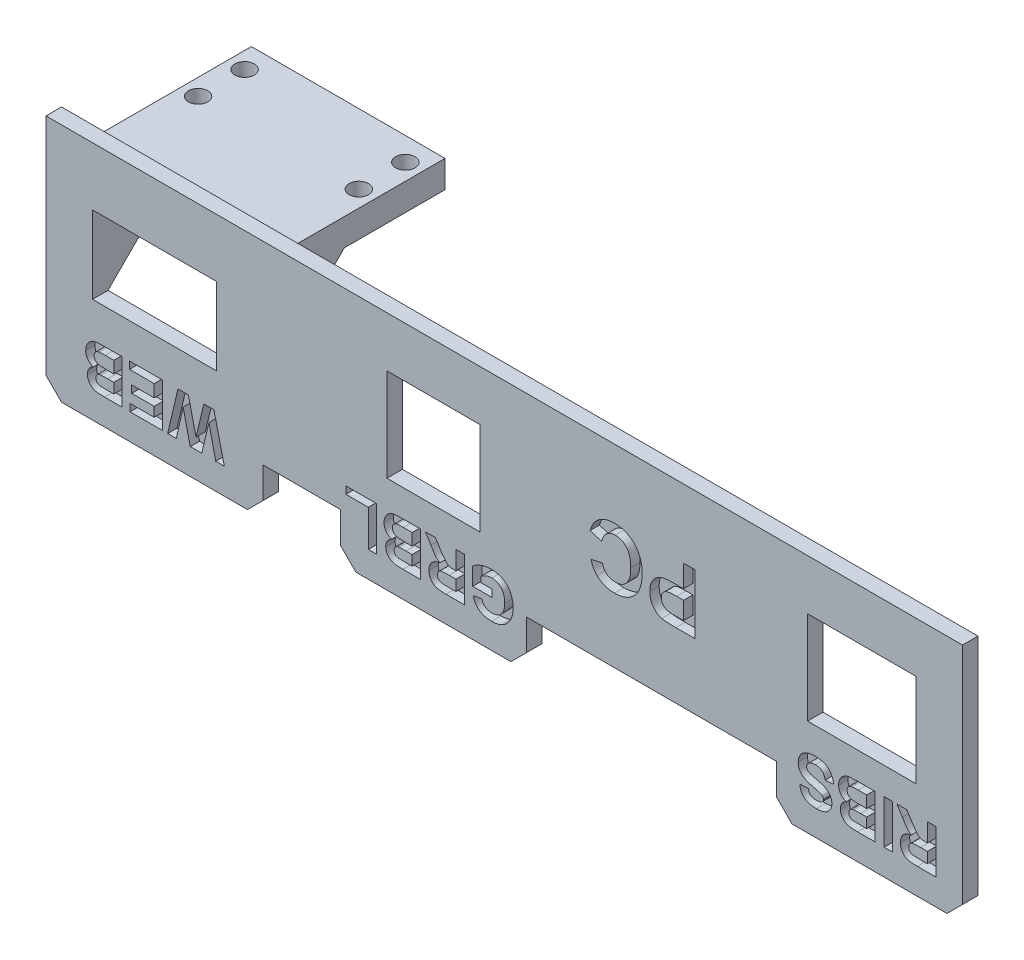
SolidWorks part; units mm, degrees
ref_plane "Спереди" through (0, 0, 0) normal (0, 0, 1) x (1, 0, 0)
ref_plane "Сверху" through (0, 0, 0) normal (0, 1, 0) x (1, 0, 0)
ref_plane "Справа" through (0, 0, 0) normal (1, 0, 0) x (0, 0, -1)
sketch "Эскиз1" plane through (0, 0, 0) normal (0, 0, 1) x (1, 0, 0)
  line L1 (-40, 12.5) -> (40, 12.5)
  line L2 (-40, 12.5) -> (-40, -12.5)
  line L3 (-40, -12.5) -> (40, -12.5)
  line L4 (40, 12.5) -> (40, -12.5)
  line L5 (-40, 12.5) -> (40, -12.5) construction
  line L6 (-40, -12.5) -> (40, 12.5) construction
  point P0 (0, 0)
  dimension "D1" = 80
  dimension "D2" = 25
extrude "Бобышка-Вытянуть1" add sketch "Эскиз1" along normal blind 2
sketch "Эскиз2" plane through (0, 0, 2) normal (0, 0, 1) x (1, 0, 0)
  line L0 (-40, 12.5) -> (27, 12.5)
  line L1 (40, 12.5) -> (-40, 12.5) construction
  line L2 (27, 12.5) -> (27, 0)
  line L3 (27, 12.5) -> (40, 12.5)
  line L4 (20, 6) -> (34, 6)
  line L5 (20, 6) -> (20, -6)
  line L6 (20, -6) -> (34, -6)
  line L7 (34, 6) -> (34, -6)
  line L8 (20, 6) -> (34, -6) construction
  line L9 (20, -6) -> (34, 6) construction
  dimension "D1" = 13
  dimension "D2" = 14
  dimension "D3" = 12
extrude "Вырез-Вытянуть2" cut sketch "Эскиз2" against normal through all
sketch "Эскиз3" plane through (0, 0, 0) normal (0, 0, -1) x (-1, 0, 0)
  line L0 (-20, -6) -> (-34, 6)
  line L1 (-27, 0) -> (28.28, 0)
  line L3 (22.28, 6) -> (34.28, 6)
  line L4 (22.28, 6) -> (22.28, -6)
  line L5 (22.28, -6) -> (34.28, -6)
  line L6 (34.28, 6) -> (34.28, -6)
  line L7 (22.28, 6) -> (34.28, -6) construction
  line L8 (22.28, -6) -> (34.28, 6) construction
  dimension "D1" = 55.28
  dimension "D2" = 12
  dimension "D3" = 12
extrude "Вырез-Вытянуть3" cut sketch "Эскиз3" against normal through all
sketch "Эскиз4" plane through (0, 0, 0) normal (0, 0, -1) x (-1, 0, 0)
  line L1 (40, 12.5) -> (80, 12.5)
  line L2 (40, 12.5) -> (40, -12.5)
  line L3 (40, -12.5) -> (80, -12.5)
  line L4 (80, 12.5) -> (80, -12.5)
  dimension "D1" = 40
extrude "Бобышка-Вытянуть2" add sketch "Эскиз4" against normal blind 2
sketch "Эскиз5" plane through (0, 0, 0) normal (0, 0, -1) x (-1, 0, 0)
  line L0 (34.28, 0) -> (64.28, 0)
  line L1 (34.28, 6) -> (34.28, -6) construction
  line L3 (56.28, 5) -> (72.28, 5)
  line L4 (56.28, 5) -> (56.28, -5)
  line L5 (56.28, -5) -> (72.28, -5)
  line L6 (72.28, 5) -> (72.28, -5)
  line L7 (56.28, 5) -> (72.28, -5) construction
  line L8 (56.28, -5) -> (72.28, 5) construction
  dimension "D1" = 30
  dimension "D2" = 10
  dimension "D3" = 16
extrude "Вырез-Вытянуть4" cut sketch "Эскиз5" against normal through all
sketch "Эскиз6" plane through (0, 0, 2) normal (0, 0, 1) x (1, 0, 0)
  line L0 (-56.28, -5) -> (-72.28, -5) construction
  line L1 (-51.78, 5) -> (-76.78, 5)
  line L2 (-51.78, 5) -> (-51.78, 8.5)
  line L3 (-51.78, 8.5) -> (-76.78, 8.5)
  line L4 (-76.78, 5) -> (-76.78, 8.5)
  line L5 (-56.28, 5) -> (-72.28, 5) construction
  point P4 (-64.28, 5)
  point P5 (-64.28, -5)
  dimension "D1" = 25
  dimension "D2" = 3.5
extrude "Бобышка-Вытянуть3" add sketch "Эскиз6" against normal blind 25
chamfer "Фаска1" distance 10 angle 45 2 edges at (-74.53, 5, 0) (-54.03, 5, 0)
sketch "Эскиз7" plane through (0, 5, 0) normal (0, -1, 0) x (1, 0, 0)
  line L0 (-51.78, -23) -> (-53.9088, -23)
  line L1 (-76.78, -23) -> (-51.78, -23) construction
  line L2 (-53.9088, -23) -> (-53.9088, -20)
  line L3 (-53.9088, -20) -> (-53.9088, -14)
  line L4 (-64.28, -23) -> (-64.28, -18.1669)
  circle A0 centre (-53.9088, -20) radius 1.25
  circle A1 centre (-53.9088, -14) radius 1.25
  circle A2 centre (-74.6512, -20) radius 1.25
  circle A3 centre (-74.6512, -14) radius 1.25
  dimension "D1" = 2.5
  dimension "D2" = 3
  dimension "D3" = 6
extrude "Вырез-Вытянуть5" cut sketch "Эскиз7" against normal through all
sketch "Эскиз8" plane through (0, 5, 0) normal (0, -1, 0) x (1, 0, 0)
  line L0 (-76.78, -23) -> (-51.78, -23) construction
  line L1 (-59.28, -23) -> (-69.28, -23)
  line L2 (-59.28, -23) -> (-59.28, -11)
  line L3 (-59.28, -11) -> (-69.28, -11)
  line L4 (-69.28, -23) -> (-69.28, -11)
  line L5 (-59.28, -23) -> (-51.78, -23)
  line M11 (-76.78, -23) -> (-51.78, -23)
  dimension "D1" = 10
  dimension "D2" = 7.5
  dimension "D3" = 12
extrude "Бобышка-Вытянуть4" add sketch "Эскиз8" along normal blind 1.5 contours L4 L2 L3 M11
sketch "Эскиз9" plane through (0, 0, 0) normal (0, 0, -1) x (-1, 0, 0)
  line L1 (76.78, 8.5) -> (80, 8.5)
  line L2 (80, -12.5) -> (80, 12.5) construction
  line L3 (80, 12.5) -> (82.78, 12.5)
  line L4 (82.78, 12.5) -> (82.78, -12.5)
  line L5 (82.78, -12.5) -> (80, -12.5)
  line L6 (80, 12.5) -> (80, -12.5)
  line M16 (80, -12.5) -> (80, 12.5)
  dimension "D1" = 2.78
extrude "Бобышка-Вытянуть5" add sketch "Эскиз9" against normal blind 2 contours L5 L4 L3 M16
sketch "Эскиз11" plane through (0, 0, 2) normal (0, 0, 1) x (1, 0, 0)
  line L0 (20, 6) -> (20, 3.6517)
  line L1 (20, 6) -> (20, -6) construction
  line L2 (20, 3.6517) -> (-22.28, 3.6517)
  line L3 (-22.28, 6) -> (-22.28, -6) construction
  line L4 (5.4784, 3.6517) -> (5.4784, -4.0532)
  line L5 (5.4784, -4.0532) -> (3.0135, -4.0532)
  line L6 (2.9826, 0.7871) -> (3.9966, 0.7871)
  line L7 (3.9966, 0.7871) -> (3.9966, 3.6517)
  line L8 (3.9966, 3.6517) -> (5.4784, 3.6517)
  line L9 (3.9966, -2.769) -> (3.9966, -0.4971)
  line L10 (3.9966, -0.4971) -> (3.1076, -0.4971)
  line L11 (3.2126, -2.769) -> (3.9966, -2.769)
  line L12 (-6.573, 0.7871) -> (-8.0547, 1.281)
  line L13 (-7.9559, -1.88) -> (-6.4742, -1.5837)
  spline S0 degree 3 poles (3.0135, -4.0532) (2.8004, -4.0541) (2.4958, -4.0501) (2.1099, -4.0372) (1.8659, -4.0258) (1.6529, -4.0088) (1.4287, -3.9845) (1.276, -3.9608) (1.186, -3.9359) knots 0 0 0 0 0.34833 0.498164 0.631258 0.747724 0.847597 1 1 1 1
  spline S1 degree 3 poles (1.186, -3.9359) (1.078, -3.9088) (0.9218, -3.8507) (0.7242, -3.7497) (0.5845, -3.6597) (0.4501, -3.559) (0.3239, -3.444) (0.2027, -3.3169) (0.0894, -3.1774) (-0.0152, -3.0261) (-0.1039, -2.8621) (-0.1803, -2.6883) (-0.2413, -2.5035) (-0.2918, -2.3089) (-0.336, -2.0278) (-0.352, -1.8106) (-0.3497, -1.6624) knots 0 0 0 0 0.112518 0.168209 0.224432 0.280596 0.338142 0.397105 0.458213 0.520063 0.583016 0.646708 0.712116 0.779846 0.850081 1 1 1 1
  spline S2 degree 3 poles (-0.3497, -1.6624) (-0.3521, -1.4412) (-0.322, -1.1202) (-0.2135, -0.719) (-0.0986, -0.4596) (0.0385, -0.2274) (0.1962, -0.0228) (0.3671, 0.1592) (0.5583, 0.3092) (0.7574, 0.4344) (1.0201, 0.5743) (1.2286, 0.6444) (1.3681, 0.676) knots 0 0 0 0 0.210528 0.305147 0.394439 0.479889 0.561317 0.639975 0.717023 0.791911 0.863787 1 1 1 1
  spline S3 degree 3 poles (1.3681, 0.676) (1.4709, 0.6962) (1.6332, 0.722) (1.8613, 0.745) (2.0553, 0.7604) (2.2653, 0.7724) (2.576, 0.7857) (2.8169, 0.7864) (2.9826, 0.7871) knots 0 0 0 0 0.193876 0.303997 0.424377 0.554128 0.693296 1 1 1 1
  spline S4 degree 3 poles (3.1076, -0.4971) (2.961, -0.4972) (2.7503, -0.4986) (2.4835, -0.5152) (2.3123, -0.5256) (2.1621, -0.5448) (2.031, -0.5655) (1.9201, -0.5913) (1.7998, -0.6296) (1.6704, -0.6903) (1.5328, -0.7803) (1.4129, -0.8892) (1.3124, -1.015) (1.2314, -1.1542) (1.1537, -1.3603) (1.1301, -1.5265) (1.132, -1.6392) knots 0 0 0 0 0.168841 0.242402 0.307726 0.366205 0.416644 0.460461 0.497174 0.561832 0.624256 0.685892 0.747405 0.808969 0.870459 1 1 1 1
  spline S5 degree 3 poles (1.132, -1.6392) (1.1295, -1.7745) (1.1613, -1.9734) (1.2711, -2.2121) (1.3855, -2.3636) (1.5232, -2.4915) (1.7343, -2.6315) (1.9172, -2.6915) (2.0426, -2.715) knots 0 0 0 0 0.263219 0.386149 0.508701 0.630747 0.750909 1 1 1 1
  spline S6 degree 3 poles (2.0426, -2.715) (2.1029, -2.7257) (2.2033, -2.7371) (2.3497, -2.7483) (2.4871, -2.7559) (2.6425, -2.7618) (2.8863, -2.7689) (3.0783, -2.7668) (3.2126, -2.769) knots 0 0 0 0 0.156655 0.258348 0.375719 0.50881 0.656332 1 1 1 1
  spline S7 degree 3 poles (-8.0547, 1.281) (-7.9986, 1.4719) (-7.9019, 1.7495) (-7.7339, 2.0943) (-7.5966, 2.3285) (-7.4444, 2.5425) (-7.2794, 2.7385) (-7.0976, 2.9133) (-6.9024, 3.07) (-6.6931, 3.2079) (-6.4698, 3.3271) (-6.2331, 3.4274) (-5.9826, 3.5092) (-5.7191, 3.5744) (-5.3414, 3.6336) (-5.0502, 3.6526) (-4.852, 3.6517) knots 0 0 0 0 0.13791 0.202925 0.265376 0.325683 0.384581 0.442536 0.500073 0.557687 0.615869 0.675098 0.735491 0.79823 0.86284 1 1 1 1
  spline S8 degree 3 poles (-4.852, 3.6517) (-4.6058, 3.6534) (-4.2424, 3.6218) (-3.7772, 3.5128) (-3.4505, 3.402) (-3.142, 3.2556) (-2.8507, 3.0776) (-2.5771, 2.8669) (-2.3218, 2.6274) (-2.0903, 2.3594) (-1.8884, 2.0651) (-1.7167, 1.7482) (-1.5772, 1.4071) (-1.4693, 1.0424) (-1.365, 0.5122) (-1.3374, 0.0981) (-1.3376, -0.1838) knots 0 0 0 0 0.126041 0.185858 0.244347 0.302332 0.360396 0.418837 0.478855 0.539381 0.599819 0.661239 0.723621 0.788224 0.855654 1 1 1 1
  spline S9 degree 3 poles (-1.3376, -0.1838) (-1.3381, -0.4808) (-1.3636, -0.9163) (-1.47, -1.4727) (-1.5744, -1.8541) (-1.7154, -2.2079) (-1.8822, -2.5377) (-2.0856, -2.8385) (-2.3145, -3.1134) (-2.5699, -3.3574) (-2.846, -3.5705) (-3.142, -3.7497) (-3.4567, -3.8983) (-3.7914, -4.0118) (-4.2725, -4.124) (-4.6495, -4.1498) (-4.9045, -4.152) knots 0 0 0 0 0.147861 0.216121 0.281505 0.344236 0.405241 0.465004 0.524411 0.582874 0.640357 0.697546 0.754672 0.813104 0.873008 1 1 1 1
  spline S10 degree 3 poles (-4.9045, -4.152) (-5.1274, -4.1499) (-5.4566, -4.1292) (-5.8782, -4.0388) (-6.1714, -3.9454) (-6.4496, -3.8288) (-6.7976, -3.6334) (-7.0329, -3.4474) (-7.1765, -3.3093) knots 0 0 0 0 0.269237 0.396245 0.519357 0.640091 0.759611 1 1 1 1
  spline S11 degree 3 poles (-7.1765, -3.3093) (-7.2664, -3.2251) (-7.3882, -3.0827) (-7.5337, -2.8745) (-7.6349, -2.7019) (-7.7277, -2.5155) (-7.843, -2.2435) (-7.9148, -2.0286) (-7.9559, -1.88) knots 0 0 0 0 0.22393 0.340378 0.462188 0.5879 0.719301 1 1 1 1
  spline S12 degree 3 poles (-6.4742, -1.5837) (-6.4516, -1.68) (-6.4071, -1.8196) (-6.329, -1.9961) (-6.2577, -2.1164) (-6.1819, -2.2319) (-6.0921, -2.3367) (-5.9957, -2.436) (-5.8887, -2.5253) (-5.7741, -2.6058) (-5.6531, -2.6766) (-5.5253, -2.7358) (-5.3917, -2.7831) (-5.2528, -2.8228) (-5.0555, -2.8565) (-4.904, -2.8703) (-4.8011, -2.8678) knots 0 0 0 0 0.129401 0.191503 0.25216 0.312317 0.372084 0.432576 0.493292 0.554214 0.615791 0.676668 0.738245 0.801163 0.865508 1 1 1 1
  spline S13 degree 3 poles (-4.8011, -2.8678) (-4.6597, -2.8695) (-4.452, -2.8488) (-4.1856, -2.7872) (-4.0002, -2.7201) (-3.826, -2.633) (-3.6604, -2.5295) (-3.5076, -2.4046) (-3.3639, -2.2624) (-3.2352, -2.0972) (-3.1219, -1.9095) (-3.028, -1.6971) (-2.9517, -1.4621) (-2.8917, -1.2039) (-2.8322, -0.8142) (-2.8216, -0.5075) (-2.8193, -0.2964) knots 0 0 0 0 0.114852 0.169049 0.221995 0.274766 0.327238 0.380498 0.43494 0.491274 0.550406 0.612776 0.679731 0.751083 0.828135 1 1 1 1
  spline S14 degree 3 poles (-2.8193, -0.2964) (-2.8217, -0.0735) (-2.8318, 0.2496) (-2.8919, 0.6603) (-2.9508, 0.9306) (-3.028, 1.1752) (-3.1221, 1.3942) (-3.2321, 1.5889) (-3.3626, 1.7558) (-3.5059, 1.8998) (-3.6586, 2.0256) (-3.8224, 2.1314) (-3.996, 2.2187) (-4.1808, 2.2846) (-4.4448, 2.35) (-4.6516, 2.3685) (-4.7918, 2.3676) knots 0 0 0 0 0.177674 0.256759 0.330211 0.397713 0.460651 0.519748 0.575226 0.628818 0.681222 0.73247 0.78377 0.835607 0.888367 1 1 1 1
  spline S15 degree 3 poles (-4.7918, 2.3676) (-4.8959, 2.3661) (-5.0513, 2.3583) (-5.2512, 2.3156) (-5.3936, 2.274) (-5.5311, 2.2217) (-5.6617, 2.1546) (-5.7877, 2.0776) (-5.9067, 1.9872) (-6.0203, 1.8858) (-6.1238, 1.7686) (-6.2199, 1.6385) (-6.3072, 1.4944) (-6.3887, 1.3378) (-6.4839, 1.1028) (-6.5426, 0.9167) (-6.573, 0.7871) knots 0 0 0 0 0.120461 0.178741 0.235724 0.291792 0.348406 0.404979 0.462271 0.52076 0.580529 0.642578 0.707405 0.77492 0.84633 1 1 1 1
extrude "Вырез-Вытянуть6" cut sketch "Эскиз11" against normal blind 1.2 contours S3 S2 S1 S0 L5 L4 L2 L7 L6 S6 S5 S4 L10 L9 L11 | S15 S14 S13 S12 L13 S11 S10 S9 S8 L2 S7 L12
sketch "Эскиз12" plane through (0, 0, 2) normal (0, 0, 1) x (1, 0, 0)
  line L0 (40, -12.5) -> (40, -18.5)
  line L1 (40, -18.5) -> (16, -18.5)
  line L2 (16, -18.5) -> (16, -12.5)
  line L3 (-82.78, -12.5) -> (40, -12.5) construction
  line L4 (16, -12.5) -> (-16.28, -12.5)
  line L5 (-16.28, -12.5) -> (-16.28, -18.5)
  line L6 (-16.28, -18.5) -> (-40.28, -18.5)
  line L7 (-40.28, -18.5) -> (-40.28, -12.5)
  line L8 (-40.28, -12.5) -> (-50.28, -12.5)
  line L9 (-50.28, -12.5) -> (-50.28, -18.5)
  line L10 (-50.28, -18.5) -> (-82.78, -18.5)
  line L11 (-82.78, -18.5) -> (-82.78, -12.5)
  line L13 (-22.28, 6) -> (-22.28, -6) construction
  line L14 (-34.28, 6) -> (-34.28, -6) construction
  line L15 (-56.28, 5) -> (-56.28, -5) construction
  line L16 (40, -12.5) -> (-82.78, -12.5)
  line M13 (-82.78, -12.5) -> (40, -12.5)
  dimension "D1" = 24
  dimension "D2" = 6
  dimension "D3" = 6
  dimension "D4" = 6
  dimension "D5" = 6
  dimension "D6" = 6
  dimension "D7" = 6
extrude "Бобышка-Вытянуть6" add sketch "Эскиз12" against normal blind 2 contours L2 L1 L0 M13 | L7 L6 L5 M13 | L11 L10 L9 M13
sketch "Эскиз13" plane through (0, 0, 2) normal (0, 0, 1) x (1, 0, 0)
  line L0 (-78.28, 12.5) -> (-78.28, -18.5)
  line L1 (40, 12.5) -> (-82.78, 12.5) construction
  line L2 (-50.28, -18.5) -> (-82.78, -18.5) construction
  line L3 (-72.28, 5) -> (-72.28, -5) construction
  line L5 (-78.28, -18.5) -> (-82.78, -18.5)
  line L6 (-78.28, -18.5) -> (-78.28, 12.5)
  line L7 (-78.28, 12.5) -> (-82.78, 12.5)
  line L8 (-82.78, -18.5) -> (-82.78, 12.5)
  line M7 (40, 12.5) -> (-82.78, 12.5)
  line M8 (-82.78, 12.5) -> (-82.78, -18.5)
  line M9 (-82.78, -18.5) -> (-50.28, -18.5)
  dimension "D1" = 6
extrude "Вырез-Вытянуть7" cut sketch "Эскиз13" against normal through all contours L0 M7 M8 M9
chamfer "Фаска2" distance 2 angle 45 6 edges at (40, -18.5, 1) (16, -18.5, 1) (-16.28, -18.5, 1) (-40.28, -18.5, 1) (-50.28, -18.5, 1) (-78.28, -18.5, 1)
sketch "Эскиз14" plane through (0, 0, 2) normal (0, 0, 1) x (1, 0, 0)
  line L5 (-16.28, -12.5) -> (-16.28, -9.5)
  line L10 (36.5479, -9.5) -> (36.5479, -15.1503)
  line L11 (36.5479, -15.1503) -> (34.1766, -15.1503)
  line L12 (32.2343, -10.6183) -> (31.5495, -9.5)
  line L13 (31.5495, -9.5) -> (32.8195, -9.5)
  line L14 (32.8195, -9.5) -> (33.6231, -10.7824)
  line L15 (35.2179, -11.8905) -> (35.4613, -11.8905)
  line L16 (35.4613, -11.8905) -> (35.4613, -9.5)
  line L17 (35.4613, -9.5) -> (36.5479, -9.5)
  line L18 (35.4613, -12.8322) -> (34.5864, -12.8322)
  line L19 (34.5377, -14.2086) -> (35.4613, -14.2086)
  line L20 (35.4613, -14.2086) -> (35.4613, -12.8322)
  line L21 (30.97, -9.5) -> (30.97, -15.1503)
  line L22 (30.97, -15.1503) -> (29.8834, -15.1503)
  line L23 (29.8834, -15.1503) -> (29.8834, -9.5)
  line L24 (29.8834, -9.5) -> (30.97, -9.5)
  line L25 (28.7244, -15.1503) -> (26.4482, -15.1503)
  line L26 (26.8115, -9.5) -> (28.7244, -9.5)
  line L27 (28.7244, -9.5) -> (28.7244, -15.1503)
  line L28 (27.6378, -14.2086) -> (27.6378, -12.9047)
  line L29 (27.6378, -12.9047) -> (26.8512, -12.9047)
  line L30 (26.9485, -14.2086) -> (27.6378, -14.2086)
  line L31 (27.6378, -11.963) -> (27.6378, -10.4417)
  line L32 (27.6378, -10.4417) -> (26.5286, -10.4417)
  line L33 (26.6701, -11.963) -> (27.6378, -11.963)
  line L34 (23.3639, -11.3834) -> (22.2773, -11.4559)
  line L35 (19.0175, -13.5566) -> (20.1041, -13.4842)
  line L36 (-20.7463, -11.6008) -> (-20.7463, -12.5425)
  line L37 (-20.7463, -12.5425) -> (-23.2092, -12.5425)
  line L38 (-23.2092, -12.5425) -> (-23.2092, -10.2731)
  line L39 (-23.1368, -13.5566) -> (-22.0502, -13.3393)
  line L40 (-22.1226, -10.8639) -> (-22.1226, -11.6008)
  line L41 (-22.1226, -11.6008) -> (-20.7463, -11.6008)
  line L42 (-24.2958, -9.5) -> (-24.2958, -15.1503)
  line L43 (-24.2958, -15.1503) -> (-26.6671, -15.1503)
  line L44 (-28.6094, -10.6183) -> (-29.2942, -9.5)
  line L45 (-29.2942, -9.5) -> (-28.0242, -9.5)
  line L46 (-28.0242, -9.5) -> (-27.2206, -10.7824)
  line L47 (-25.6258, -11.8905) -> (-25.3824, -11.8905)
  line L48 (-25.3824, -11.8905) -> (-25.3824, -9.5)
  line L49 (-25.3824, -9.5) -> (-24.2958, -9.5)
  line L50 (-25.3824, -12.8322) -> (-26.2573, -12.8322)
  line L51 (-26.306, -14.2086) -> (-25.3824, -14.2086)
  line L52 (-25.3824, -14.2086) -> (-25.3824, -12.8322)
  line L53 (-29.9461, -15.1503) -> (-32.2223, -15.1503)
  line L54 (-31.859, -9.5) -> (-29.9461, -9.5)
  line L55 (-29.9461, -9.5) -> (-29.9461, -15.1503)
  line L56 (-31.0327, -14.2086) -> (-31.0327, -12.9047)
  line L57 (-31.0327, -12.9047) -> (-31.8194, -12.9047)
  line L58 (-31.722, -14.2086) -> (-31.0327, -14.2086)
  line L59 (-31.0327, -11.963) -> (-31.0327, -10.4417)
  line L60 (-31.0327, -10.4417) -> (-32.1419, -10.4417)
  line L61 (-32.0005, -11.963) -> (-31.0327, -11.963)
  line L62 (-35.5964, -9.5) -> (-35.5964, -15.1503)
  line L63 (-35.5964, -15.1503) -> (-36.683, -15.1503)
  line L64 (-36.683, -15.1503) -> (-36.683, -10.4417)
  line L65 (-36.683, -10.4417) -> (-39.5806, -10.4417)
  line L66 (-39.5806, -10.4417) -> (-39.5806, -9.5)
  line L67 (-39.5806, -9.5) -> (-35.5964, -9.5)
  line L68 (-56.6138, -9.5) -> (-55.2613, -15.1503)
  line L69 (-55.2613, -15.1503) -> (-56.375, -15.1503)
  line L70 (-56.375, -15.1503) -> (-57.2533, -11.2691)
  line L71 (-57.2533, -11.2691) -> (-58.1826, -15.1503)
  line L72 (-58.1826, -15.1503) -> (-59.6654, -15.1503)
  line L73 (-59.6654, -15.1503) -> (-60.5856, -11.2035)
  line L74 (-60.5856, -11.2035) -> (-61.4616, -15.1503)
  line L75 (-61.4616, -15.1503) -> (-62.5777, -15.1503)
  line L76 (-62.5777, -15.1503) -> (-61.25, -9.5)
  line L77 (-61.25, -9.5) -> (-59.9042, -9.5)
  line L78 (-59.9042, -9.5) -> (-58.9195, -13.7241)
  line L79 (-58.9195, -13.7241) -> (-57.9087, -9.5)
  line L80 (-57.9087, -9.5) -> (-56.6138, -9.5)
  line L81 (-63.2296, -9.5) -> (-63.2296, -15.1503)
  line L82 (-63.2296, -15.1503) -> (-67.4311, -15.1503)
  line L83 (-67.4311, -15.1503) -> (-67.4311, -14.2086)
  line L84 (-67.4311, -14.2086) -> (-64.3162, -14.2086)
  line L85 (-64.3162, -14.2086) -> (-64.3162, -12.9771)
  line L86 (-64.3162, -12.9771) -> (-67.2138, -12.9771)
  line L87 (-67.2138, -12.9771) -> (-67.2138, -12.0354)
  line L88 (-67.2138, -12.0354) -> (-64.3162, -12.0354)
  line L89 (-64.3162, -12.0354) -> (-64.3162, -10.4417)
  line L90 (-64.3162, -10.4417) -> (-67.5036, -10.4417)
  line L91 (-67.5036, -10.4417) -> (-67.5036, -9.5)
  line L92 (-67.5036, -9.5) -> (-63.2296, -9.5)
  line L93 (-68.4453, -15.1503) -> (-70.7215, -15.1503)
  line L94 (-70.3581, -9.5) -> (-68.4453, -9.5)
  line L95 (-68.4453, -9.5) -> (-68.4453, -15.1503)
  line L96 (-69.5319, -14.2086) -> (-69.5319, -12.9047)
  line L97 (-69.5319, -12.9047) -> (-70.3185, -12.9047)
  line L98 (-70.2212, -14.2086) -> (-69.5319, -14.2086)
  line L99 (-69.5319, -11.963) -> (-69.5319, -10.4417)
  line L100 (-69.5319, -10.4417) -> (-70.6411, -10.4417)
  line L101 (-70.4996, -11.963) -> (-69.5319, -11.963)
  line L102 (-25.3824, -12.8322) -> (-25.3824, -14.2086)
  spline S0 degree 3 poles (34.1766, -15.1503) (34.0378, -15.1496) (33.8367, -15.1479) (33.5796, -15.1297) (33.4092, -15.1149) (33.254, -15.0932) (33.1138, -15.0677) (32.9889, -15.0375) (32.878, -15.002) (32.7772, -14.9605) (32.6831, -14.912) (32.5946, -14.8548) (32.5106, -14.7912) (32.4309, -14.7211) (32.3574, -14.6427) (32.2891, -14.557) (32.226, -14.4649) (32.1703, -14.3667) (32.1195, -14.2656) (32.0781, -14.1605) (32.0439, -14.0519) (32.0166, -13.9401) (31.9909, -13.7844) (31.9837, -13.6651) (31.9842, -13.5849) knots 0 0 0 0 0.134565 0.194651 0.249722 0.300282 0.346384 0.387789 0.424666 0.459085 0.493256 0.527124 0.561048 0.595231 0.629883 0.664994 0.701292 0.737973 0.774267 0.810855 0.847273 0.884511 0.922312 1 1 1 1
  spline S1 degree 3 poles (31.9842, -13.5849) (31.9835, -13.4845) (31.9956, -13.3366) (32.0312, -13.1452) (32.0714, -13.0117) (32.1214, -12.8847) (32.1824, -12.7649) (32.2545, -12.6514) (32.3379, -12.5456) (32.4324, -12.4474) (32.5384, -12.3589) (32.6553, -12.2791) (32.784, -12.2106) (32.9224, -12.1502) (33.1272, -12.0822) (33.2895, -12.0483) (33.4013, -12.0309) knots 0 0 0 0 0.129371 0.190807 0.250677 0.308758 0.366624 0.423704 0.481897 0.540034 0.599076 0.659654 0.722117 0.786819 0.85404 1 1 1 1
  spline S2 degree 3 poles (33.4013, -12.0309) (33.2918, -11.9619) (33.1381, -11.8489) (32.9546, -11.6812) (32.8514, -11.572) (32.775, -11.4742) (32.7109, -11.3905) (32.6432, -11.2928) (32.5716, -11.1818) (32.4927, -11.0596) (32.3788, -10.8709) (32.2926, -10.7221) (32.2343, -10.6183) knots 0 0 0 0 0.209166 0.307622 0.401733 0.451661 0.508279 0.572256 0.643667 0.721858 0.807553 1 1 1 1
  spline S3 degree 3 poles (33.6231, -10.7824) (33.6933, -10.8807) (33.7949, -11.0201) (33.9245, -11.1957) (34.0094, -11.304) (34.0817, -11.3999) (34.148, -11.4784) (34.2029, -11.5441) (34.2653, -11.609) (34.3373, -11.6763) (34.4281, -11.7389) (34.5184, -11.793) (34.6178, -11.8319) (34.7323, -11.8591) (34.9337, -11.8851) (35.0989, -11.8919) (35.2179, -11.8905) knots 0 0 0 0 0.174866 0.24983 0.316058 0.374091 0.423761 0.464831 0.498066 0.554153 0.607062 0.657484 0.706287 0.760884 0.827646 1 1 1 1
  spline S4 degree 3 poles (34.5864, -12.8322) (34.4577, -12.8315) (34.2747, -12.8352) (34.0441, -12.84) (33.9011, -12.8487) (33.778, -12.8569) (33.6749, -12.868) (33.5916, -12.8809) (33.5084, -12.9011) (33.4232, -12.9362) (33.3325, -12.9863) (33.2543, -13.0511) (33.1884, -13.1272) (33.1356, -13.2143) (33.0838, -13.3489) (33.0713, -13.4597) (33.0708, -13.5351) knots 0 0 0 0 0.202213 0.28763 0.362457 0.427262 0.481544 0.52541 0.559637 0.615792 0.669702 0.721935 0.77448 0.827155 0.881221 1 1 1 1
  spline S5 degree 3 poles (33.0708, -13.5351) (33.0711, -13.6189) (33.0878, -13.7423) (33.1552, -13.889) (33.2257, -13.9808) (33.3146, -14.0575) (33.4602, -14.1422) (33.5866, -14.1764) (33.6741, -14.1905) knots 0 0 0 0 0.256156 0.373043 0.488836 0.606317 0.729101 1 1 1 1
  spline S6 degree 3 poles (33.6741, -14.1905) (33.7098, -14.1952) (33.7729, -14.198) (33.8687, -14.2024) (33.968, -14.2041) (34.0849, -14.2068) (34.277, -14.2076) (34.4298, -14.2095) (34.5377, -14.2086) knots 0 0 0 0 0.124813 0.21921 0.333205 0.469464 0.625352 1 1 1 1
  spline S7 degree 3 poles (26.4482, -15.1503) (26.3426, -15.1494) (26.1893, -15.1494) (25.9924, -15.1426) (25.8607, -15.1374) (25.7399, -15.1297) (25.6298, -15.1193) (25.5305, -15.1081) (25.4131, -15.0924) (25.2776, -15.0615) (25.1238, -15.0108) (24.979, -14.9444) (24.8424, -14.8643) (24.7163, -14.7676) (24.6018, -14.6556) (24.4965, -14.5304) (24.4044, -14.391) (24.3276, -14.2393) (24.2547, -14.0198) (24.2329, -13.8458) (24.2331, -13.7287) knots 0 0 0 0 0.10585 0.153503 0.197393 0.237927 0.274751 0.30823 0.338007 0.393399 0.447191 0.499968 0.552674 0.605523 0.65872 0.712927 0.769123 0.825755 0.882774 1 1 1 1
  spline S8 degree 3 poles (24.2331, -13.7287) (24.2311, -13.5996) (24.2596, -13.4085) (24.3445, -13.1663) (24.4356, -12.9979) (24.5467, -12.8424) (24.7243, -12.6612) (24.8829, -12.555) (24.9983, -12.5029) knots 0 0 0 0 0.253072 0.37677 0.502927 0.628361 0.751685 1 1 1 1
  spline S9 degree 3 poles (24.9983, -12.5029) (24.9222, -12.4782) (24.8114, -12.436) (24.6743, -12.3617) (24.5796, -12.3009) (24.491, -12.2339) (24.4113, -12.1583) (24.3357, -12.0786) (24.2693, -11.9906) (24.2093, -11.8987) (24.1583, -11.8013) (24.1141, -11.7008) (24.0772, -11.5962) (24.0509, -11.4868) (24.0224, -11.3346) (24.0174, -11.2167) (24.0158, -11.1378) knots 0 0 0 0 0.132557 0.19578 0.258217 0.318868 0.379478 0.440087 0.500739 0.561785 0.621919 0.682673 0.743576 0.805446 0.868975 1 1 1 1
  spline S10 degree 3 poles (24.0158, -11.1378) (24.0165, -11.01) (24.0378, -10.8173) (24.1126, -10.5689) (24.1903, -10.3872) (24.2862, -10.2148) (24.4011, -10.0592) (24.5314, -9.9213) (24.6786, -9.8027) (24.8434, -9.7029) (25.0946, -9.5964) (25.3004, -9.5535) (25.442, -9.5385) knots 0 0 0 0 0.162582 0.244721 0.329221 0.413447 0.495126 0.574555 0.654073 0.734809 0.818867 1 1 1 1
  spline S11 degree 3 poles (25.442, -9.5385) (25.506, -9.5328) (25.6146, -9.525) (25.7762, -9.5189) (25.9347, -9.5129) (26.1184, -9.5086) (26.4135, -9.5043) (26.6474, -9.5005) (26.8115, -9.5) knots 0 0 0 0 0.140766 0.238316 0.354022 0.487867 0.640687 1 1 1 1
  spline S12 degree 3 poles (26.8512, -12.9047) (26.7455, -12.9038) (26.5953, -12.9055) (26.4059, -12.9066) (26.2886, -12.9087) (26.1879, -12.9123) (26.0871, -12.9164) (26.0198, -12.9194) (25.9807, -12.9239) knots 0 0 0 0 0.363929 0.517302 0.652498 0.76824 0.864499 1 1 1 1
  spline S13 degree 3 poles (25.9807, -12.9239) (25.8867, -12.9355) (25.7503, -12.9645) (25.5906, -13.0463) (25.4938, -13.1228) (25.4146, -13.2128) (25.3391, -13.3579) (25.3198, -13.4819) (25.3197, -13.5657) knots 0 0 0 0 0.279096 0.404007 0.523952 0.639469 0.753487 1 1 1 1
  spline S14 degree 3 poles (25.3197, -13.5657) (25.318, -13.6464) (25.3369, -13.7641) (25.4012, -13.9053) (25.469, -13.9948) (25.5567, -14.0688) (25.7039, -14.1512) (25.834, -14.1769) (25.923, -14.1893) knots 0 0 0 0 0.250494 0.364336 0.479021 0.596291 0.718617 1 1 1 1
  spline S15 degree 3 poles (25.923, -14.1893) (25.9667, -14.194) (26.0426, -14.1969) (26.1581, -14.201) (26.2758, -14.2045) (26.4146, -14.2067) (26.641, -14.2077) (26.8213, -14.2095) (26.9485, -14.2086) knots 0 0 0 0 0.12824 0.222081 0.337978 0.472602 0.628175 1 1 1 1
  spline S16 degree 3 poles (26.5286, -10.4417) (26.4304, -10.4399) (26.2905, -10.4437) (26.1139, -10.4453) (26.0034, -10.4507) (25.9079, -10.4547) (25.8098, -10.4608) (25.7444, -10.4704) (25.7057, -10.4768) knots 0 0 0 0 0.356994 0.509418 0.64271 0.759541 0.857263 1 1 1 1
  spline S17 degree 3 poles (25.7057, -10.4768) (25.6212, -10.4903) (25.5005, -10.5308) (25.3579, -10.6188) (25.2675, -10.7018) (25.1917, -10.7998) (25.12, -10.9601) (25.1013, -11.0945) (25.1024, -11.1865) knots 0 0 0 0 0.250355 0.369204 0.489075 0.608393 0.730225 1 1 1 1
  spline S18 degree 3 poles (25.1024, -11.1865) (25.1012, -11.2669) (25.1178, -11.3843) (25.1714, -11.5293) (25.2288, -11.6243) (25.3024, -11.7073) (25.3894, -11.7798) (25.4918, -11.8387) (25.5892, -11.8778) (25.6815, -11.9034) (25.7704, -11.9177) (25.8766, -11.9331) (26.001, -11.9433) (26.1429, -11.9529) (26.3678, -11.9593) (26.5455, -11.9644) (26.6701, -11.963) knots 0 0 0 0 0.120653 0.176517 0.231509 0.286607 0.342632 0.401132 0.463522 0.500008 0.544982 0.598838 0.661524 0.732611 0.812684 1 1 1 1
  spline S19 degree 3 poles (22.2773, -11.4559) (22.2628, -11.3671) (22.23, -11.2399) (22.1731, -11.079) (22.1245, -10.971) (22.0687, -10.8725) (22.0082, -10.7818) (21.9383, -10.7027) (21.863, -10.6317) (21.7813, -10.569) (21.6922, -10.5157) (21.5967, -10.4704) (21.4945, -10.4327) (21.3848, -10.4047) (21.2261, -10.3773) (21.1026, -10.3696) (21.0186, -10.3693) knots 0 0 0 0 0.146276 0.213514 0.277578 0.338921 0.39771 0.454752 0.510385 0.566047 0.621994 0.679152 0.738044 0.798989 0.863227 1 1 1 1
  spline S20 degree 3 poles (21.0186, -10.3693) (20.9305, -10.3685) (20.8023, -10.376) (20.6381, -10.3999) (20.5278, -10.4263) (20.4258, -10.4588) (20.3321, -10.4982) (20.2475, -10.5461) (20.1721, -10.6015) (20.1058, -10.6615) (20.047, -10.7231) (19.9969, -10.7871) (19.9571, -10.8552) (19.9249, -10.9247) (19.8962, -11.0224) (19.8864, -11.098) (19.8867, -11.1491) knots 0 0 0 0 0.172384 0.250803 0.324407 0.39422 0.460047 0.52287 0.584156 0.642712 0.697553 0.750717 0.801367 0.851595 0.900179 1 1 1 1
  spline S21 degree 3 poles (19.8867, -11.1491) (19.8884, -11.2115) (19.899, -11.3059) (19.9518, -11.4175) (20.0032, -11.4951) (20.0766, -11.5639) (20.2104, -11.6549) (20.3306, -11.7042) (20.4165, -11.7354) knots 0 0 0 0 0.221105 0.326256 0.432309 0.546856 0.677592 1 1 1 1
  spline S22 degree 3 poles (20.4165, -11.7354) (20.46, -11.7509) (20.5347, -11.7719) (20.6449, -11.8041) (20.7516, -11.8333) (20.8746, -11.8644) (21.0694, -11.9168) (21.225, -11.9524) (21.3333, -11.9811) knots 0 0 0 0 0.14597 0.245216 0.362649 0.495673 0.646053 1 1 1 1
  spline S23 degree 3 poles (21.3333, -11.9811) (21.4769, -12.0146) (21.6823, -12.0739) (21.9421, -12.1625) (22.1131, -12.2287) (22.2661, -12.3001) (22.44, -12.395) (22.5567, -12.4764) (22.6247, -12.5357) knots 0 0 0 0 0.312029 0.452186 0.580902 0.699868 0.809232 1 1 1 1
  spline S24 degree 3 poles (22.6247, -12.5357) (22.7074, -12.6101) (22.8228, -12.7287) (22.9447, -12.9082) (23.0189, -13.0465) (23.0758, -13.1917) (23.1307, -13.3955) (23.1474, -13.5547) (23.1465, -13.6619) knots 0 0 0 0 0.260864 0.384835 0.506941 0.627504 0.749214 1 1 1 1
  spline S25 degree 3 poles (23.1465, -13.6619) (23.1472, -13.8015) (23.1167, -14.0114) (23.015, -14.2749) (22.9293, -14.4328) (22.8455, -14.5519) (22.7764, -14.6379) (22.6991, -14.7166) (22.6162, -14.7907) (22.5265, -14.8589) (22.4298, -14.9205) (22.3279, -14.9794) (22.1792, -15.047) (21.9785, -15.1192) (21.6173, -15.2032) (21.3301, -15.2218) (21.1329, -15.2227) knots 0 0 0 0 0.146322 0.219577 0.295356 0.33399 0.372238 0.410847 0.449518 0.488765 0.528819 0.569745 0.61205 0.699899 0.792982 1 1 1 1
  spline S26 degree 3 poles (21.1329, -15.2227) (20.97, -15.2234) (20.7327, -15.2104) (20.4294, -15.1633) (20.2252, -15.1134) (20.0369, -15.049) (19.8641, -14.9712) (19.7072, -14.8792) (19.5679, -14.7722) (19.4438, -14.6541) (19.3355, -14.5252) (19.2427, -14.387) (19.1647, -14.2397) (19.1035, -14.0824) (19.0422, -13.8557) (19.0225, -13.6774) (19.0175, -13.5566) knots 0 0 0 0 0.161085 0.234352 0.303094 0.368548 0.430801 0.490155 0.547887 0.604071 0.659126 0.713946 0.768328 0.823593 0.880407 1 1 1 1
  spline S27 degree 3 poles (20.1041, -13.4842) (20.1147, -13.5509) (20.1379, -13.6469) (20.1789, -13.7678) (20.2148, -13.8484) (20.2545, -13.9219) (20.3019, -13.9868) (20.353, -14.0452) (20.4097, -14.0971) (20.4747, -14.1398) (20.5446, -14.1789) (20.6227, -14.2104) (20.7079, -14.2364) (20.8007, -14.2563) (20.9382, -14.277) (21.0458, -14.2795) (21.1194, -14.281) knots 0 0 0 0 0.140144 0.204813 0.264794 0.32301 0.378021 0.431309 0.484012 0.537035 0.592435 0.650051 0.711513 0.777288 0.846983 1 1 1 1
  spline S28 degree 3 poles (21.1194, -14.281) (21.1964, -14.2801) (21.3092, -14.2762) (21.4538, -14.254) (21.5528, -14.2331) (21.6452, -14.2045) (21.7575, -14.1591) (21.8347, -14.114) (21.8822, -14.0807) knots 0 0 0 0 0.288592 0.421401 0.547152 0.666859 0.782766 1 1 1 1
  spline S29 degree 3 poles (21.8822, -14.0807) (21.9372, -14.0424) (22.0325, -13.9406) (22.0597, -13.804) (22.0599, -13.7377) knots 0 0 0 0 0.502502 1 1 1 1
  spline S30 degree 3 poles (22.0599, -13.7377) (22.0614, -13.6747) (22.03, -13.545) (21.9439, -13.4436) (21.8924, -13.4016) knots 0 0 0 0 0.485261 1 1 1 1
  spline S31 degree 3 poles (21.8924, -13.4016) (21.8488, -13.3643) (21.7666, -13.318) (21.6416, -13.2625) (21.5213, -13.2164) (21.3824, -13.1692) (21.2243, -13.1215) (21.0469, -13.0748) (20.8558, -13.0274) (20.6614, -12.9815) (20.476, -12.9311) (20.3036, -12.882) (20.145, -12.8305) (19.9994, -12.7804) (19.8675, -12.729) (19.7483, -12.6788) (19.6094, -12.6099) (19.452, -12.5166) (19.2868, -12.3809) (19.1414, -12.2284) (19.039, -12.0855) (18.9694, -11.9619) (18.9241, -11.8631) (18.8857, -11.7586) (18.8538, -11.649) (18.8309, -11.5341) (18.805, -11.3716) (18.8009, -11.2458) (18.8002, -11.1605) knots 0 0 0 0 0.041005 0.067459 0.098272 0.13351 0.172877 0.216939 0.265268 0.314388 0.360423 0.403324 0.443192 0.480233 0.513965 0.544936 0.573065 0.625373 0.676057 0.72611 0.776442 0.801932 0.827893 0.854484 0.881856 0.909824 0.938619 1 1 1 1
  spline S32 degree 3 poles (18.8002, -11.1605) (18.8004, -11.081) (18.8089, -10.9624) (18.8359, -10.8071) (18.8655, -10.6932) (18.9045, -10.5816) (18.9494, -10.4711) (19.0044, -10.3631) (19.0674, -10.2578) (19.1368, -10.1555) (19.2155, -10.0609) (19.2993, -9.9715) (19.3913, -9.8906) (19.4894, -9.8151) (19.5943, -9.746) (19.7071, -9.6851) (19.8264, -9.6302) (19.9535, -9.5834) (20.0874, -9.5409) (20.2293, -9.5064) (20.3784, -9.4768) (20.5352, -9.4543) (20.7589, -9.4329) (20.931, -9.4283) (21.048, -9.4276) knots 0 0 0 0 0.074523 0.111165 0.147718 0.184749 0.221868 0.259523 0.298231 0.336894 0.375351 0.413387 0.451726 0.490077 0.529424 0.569318 0.610161 0.652478 0.696226 0.741787 0.789382 0.838712 0.890247 1 1 1 1
  spline S33 degree 3 poles (21.048, -9.4276) (21.2156, -9.4272) (21.4603, -9.4419) (21.7736, -9.4938) (21.9868, -9.5478) (22.1841, -9.6193) (22.3662, -9.7053) (22.5335, -9.8064) (22.6844, -9.925) (22.8207, -10.058) (22.943, -10.2049) (23.049, -10.3669) (23.1431, -10.5417) (23.2189, -10.7326) (23.3082, -11.0106) (23.345, -11.2324) (23.3639, -11.3834) knots 0 0 0 0 0.14823 0.216267 0.280702 0.342464 0.401583 0.458651 0.515 0.570936 0.626873 0.683709 0.741939 0.802119 0.865135 1 1 1 1
  spline S34 degree 3 poles (-23.2092, -10.2731) (-23.1467, -10.2151) (-23.0461, -10.1309) (-22.8976, -10.0308) (-22.7741, -9.9561) (-22.6405, -9.884) (-22.4975, -9.8137) (-22.3447, -9.7457) (-22.1285, -9.6607) (-21.8509, -9.5665) (-21.3991, -9.4595) (-21.0536, -9.4276) (-20.8244, -9.4276) knots 0 0 0 0 0.099096 0.152131 0.208015 0.266887 0.328474 0.393264 0.461185 0.598484 0.733687 1 1 1 1
  spline S35 degree 3 poles (-20.8244, -9.4276) (-20.6831, -9.4282) (-20.4735, -9.437) (-20.2009, -9.4778) (-20.0058, -9.5163) (-19.8185, -9.5692) (-19.6377, -9.632) (-19.4648, -9.7087) (-19.2979, -9.7938) (-19.1411, -9.892) (-18.9916, -9.9974) (-18.855, -10.1167) (-18.726, -10.2427) (-18.6099, -10.3811) (-18.5009, -10.5269) (-18.4057, -10.6852) (-18.3186, -10.8511) (-18.2417, -11.0238) (-18.1767, -11.202) (-18.1197, -11.3831) (-18.0729, -11.5678) (-18.0385, -11.7566) (-18.0024, -12.0149) (-17.9951, -12.2122) (-17.9936, -12.3444) knots 0 0 0 0 0.092392 0.136751 0.180034 0.222274 0.263843 0.30503 0.345837 0.386144 0.425903 0.465247 0.50448 0.543665 0.58317 0.623347 0.664268 0.705555 0.746828 0.788164 0.829611 0.871252 0.913555 1 1 1 1
  spline S36 degree 3 poles (-17.9936, -12.3444) (-17.9933, -12.4865) (-18.0045, -12.6972) (-18.0417, -12.9726) (-18.0835, -13.17) (-18.1335, -13.3621) (-18.1979, -13.5476) (-18.2705, -13.7283) (-18.3572, -13.901) (-18.4526, -14.0667) (-18.5606, -14.2219) (-18.679, -14.3672) (-18.8065, -14.5039) (-18.9469, -14.6283) (-19.1483, -14.7839) (-19.312, -14.8854) (-19.4276, -14.9432) knots 0 0 0 0 0.136161 0.201853 0.266083 0.329303 0.391947 0.45404 0.515795 0.576864 0.637129 0.696747 0.75633 0.815979 0.876281 1 1 1 1
  spline S37 degree 3 poles (-19.4276, -14.9432) (-19.519, -14.9914) (-19.6645, -15.0521) (-19.8678, -15.1167) (-20.0315, -15.1544) (-20.2027, -15.1848) (-20.4468, -15.2165) (-20.6353, -15.2214) (-20.7632, -15.2227) knots 0 0 0 0 0.224671 0.342653 0.464225 0.590263 0.721121 1 1 1 1
  spline S38 degree 3 poles (-20.7632, -15.2227) (-20.9268, -15.2223) (-21.1666, -15.2119) (-21.4744, -15.1637) (-21.6853, -15.1155) (-21.882, -15.0535) (-22.0641, -14.9772) (-22.2329, -14.8883) (-22.3858, -14.7831) (-22.5259, -14.6672) (-22.653, -14.5403) (-22.7669, -14.4022) (-22.8679, -14.2538) (-22.955, -14.0943) (-23.0568, -13.8654) (-23.1093, -13.682) (-23.1368, -13.5566) knots 0 0 0 0 0.154508 0.225881 0.293868 0.358517 0.420293 0.480039 0.538219 0.595126 0.651534 0.707437 0.763839 0.820741 0.878777 1 1 1 1
  spline S39 degree 3 poles (-22.0502, -13.3393) (-22.0305, -13.4101) (-21.9935, -13.5128) (-21.9299, -13.6416) (-21.8744, -13.7301) (-21.8154, -13.8148) (-21.7461, -13.8912) (-21.6732, -13.9648) (-21.5913, -14.0299) (-21.5041, -14.0885) (-21.4124, -14.1414) (-21.3143, -14.1843) (-21.211, -14.2189) (-21.1032, -14.2482) (-20.9486, -14.2729) (-20.8296, -14.2826) (-20.7485, -14.281) knots 0 0 0 0 0.126737 0.187877 0.247501 0.306757 0.365795 0.42518 0.48537 0.545858 0.6065 0.667709 0.730295 0.794247 0.860282 1 1 1 1
  spline S40 degree 3 poles (-20.7485, -14.281) (-20.6271, -14.2795) (-20.448, -14.2688) (-20.2196, -14.2173) (-20.0618, -14.1653) (-19.9132, -14.0987) (-19.776, -14.0148) (-19.6467, -13.9186) (-19.529, -13.8058) (-19.4222, -13.6792) (-19.3298, -13.5375) (-19.2529, -13.381) (-19.1898, -13.2106) (-19.1397, -13.0262) (-19.0926, -12.7523) (-19.0794, -12.538) (-19.0802, -12.3908) knots 0 0 0 0 0.127318 0.186832 0.24467 0.301065 0.356888 0.412745 0.469466 0.527226 0.585734 0.646153 0.709402 0.775714 0.845921 1 1 1 1
  spline S41 degree 3 poles (-19.0802, -12.3908) (-19.0799, -12.2324) (-19.0916, -12.0017) (-19.1408, -11.7072) (-19.1921, -11.5093) (-19.2555, -11.3263) (-19.3356, -11.1595) (-19.4291, -11.0082) (-19.5379, -10.8741) (-19.6568, -10.7547) (-19.786, -10.6514) (-19.9245, -10.5648) (-20.0711, -10.4929) (-20.2272, -10.4373) (-20.4515, -10.3835) (-20.6272, -10.3693) (-20.7463, -10.3693) knots 0 0 0 0 0.160146 0.232866 0.3014 0.366528 0.428269 0.488051 0.545818 0.602442 0.658065 0.712552 0.767296 0.822778 0.879659 1 1 1 1
  spline S42 degree 3 poles (-20.7463, -10.3693) (-20.8701, -10.3691) (-21.0574, -10.3883) (-21.3034, -10.4483) (-21.4867, -10.5119) (-21.6636, -10.5867) (-21.8801, -10.6968) (-22.0315, -10.7913) (-22.1226, -10.8639) knots 0 0 0 0 0.249675 0.37819 0.510124 0.640779 0.765393 1 1 1 1
  spline S43 degree 3 poles (-26.6671, -15.1503) (-26.8059, -15.1496) (-27.007, -15.1479) (-27.2641, -15.1297) (-27.4346, -15.1149) (-27.5897, -15.0932) (-27.73, -15.0677) (-27.8548, -15.0375) (-27.9657, -15.002) (-28.0665, -14.9605) (-28.1606, -14.912) (-28.2491, -14.8548) (-28.3331, -14.7912) (-28.4129, -14.7211) (-28.4863, -14.6427) (-28.5546, -14.557) (-28.6177, -14.4649) (-28.6734, -14.3667) (-28.7242, -14.2656) (-28.7656, -14.1605) (-28.7998, -14.0519) (-28.8271, -13.9401) (-28.8528, -13.7844) (-28.86, -13.6651) (-28.8595, -13.5849) knots 0 0 0 0 0.134565 0.194651 0.249722 0.300282 0.346384 0.387789 0.424666 0.459085 0.493256 0.527124 0.561048 0.595231 0.629883 0.664994 0.701292 0.737973 0.774267 0.810855 0.847273 0.884511 0.922312 1 1 1 1
  spline S44 degree 3 poles (-28.8595, -13.5849) (-28.8602, -13.4845) (-28.8481, -13.3366) (-28.8125, -13.1452) (-28.7723, -13.0117) (-28.7224, -12.8847) (-28.6613, -12.7649) (-28.5892, -12.6514) (-28.5058, -12.5456) (-28.4113, -12.4474) (-28.3053, -12.3589) (-28.1884, -12.2791) (-28.0597, -12.2106) (-27.9213, -12.1502) (-27.7165, -12.0822) (-27.5542, -12.0483) (-27.4424, -12.0309) knots 0 0 0 0 0.129371 0.190807 0.250677 0.308758 0.366624 0.423704 0.481897 0.540034 0.599076 0.659654 0.722117 0.786819 0.85404 1 1 1 1
  spline S45 degree 3 poles (-27.4424, -12.0309) (-27.5519, -11.9619) (-27.7056, -11.8489) (-27.8891, -11.6812) (-27.9923, -11.572) (-28.0687, -11.4742) (-28.1329, -11.3905) (-28.2005, -11.2928) (-28.2721, -11.1818) (-28.351, -11.0596) (-28.4649, -10.8709) (-28.5511, -10.7221) (-28.6094, -10.6183) knots 0 0 0 0 0.209166 0.307622 0.401733 0.451661 0.508279 0.572256 0.643667 0.721858 0.807553 1 1 1 1
  spline S46 degree 3 poles (-27.2206, -10.7824) (-27.1504, -10.8807) (-27.0489, -11.0201) (-26.9192, -11.1957) (-26.8343, -11.304) (-26.762, -11.3999) (-26.6958, -11.4784) (-26.6408, -11.5441) (-26.5784, -11.609) (-26.5064, -11.6763) (-26.4156, -11.7389) (-26.3253, -11.793) (-26.2259, -11.8319) (-26.1114, -11.8591) (-25.91, -11.8851) (-25.7448, -11.8919) (-25.6258, -11.8905) knots 0 0 0 0 0.174866 0.24983 0.316058 0.374091 0.423761 0.464831 0.498066 0.554153 0.607062 0.657484 0.706287 0.760884 0.827646 1 1 1 1
  spline S47 degree 3 poles (-26.2573, -12.8322) (-26.386, -12.8315) (-26.569, -12.8352) (-26.7996, -12.84) (-26.9426, -12.8487) (-27.0657, -12.8569) (-27.1688, -12.868) (-27.2521, -12.8809) (-27.3353, -12.9011) (-27.4205, -12.9362) (-27.5112, -12.9863) (-27.5894, -13.0511) (-27.6553, -13.1272) (-27.7081, -13.2143) (-27.7599, -13.3489) (-27.7724, -13.4597) (-27.7729, -13.5351) knots 0 0 0 0 0.202213 0.28763 0.362457 0.427262 0.481544 0.52541 0.559637 0.615792 0.669702 0.721935 0.77448 0.827155 0.881221 1 1 1 1
  spline S48 degree 3 poles (-27.7729, -13.5351) (-27.7726, -13.6189) (-27.7559, -13.7423) (-27.6885, -13.889) (-27.618, -13.9808) (-27.5291, -14.0575) (-27.3835, -14.1422) (-27.2571, -14.1764) (-27.1696, -14.1905) knots 0 0 0 0 0.256156 0.373043 0.488836 0.606317 0.729101 1 1 1 1
  spline S49 degree 3 poles (-27.1696, -14.1905) (-27.134, -14.1952) (-27.0709, -14.198) (-26.975, -14.2024) (-26.8757, -14.2041) (-26.7588, -14.2068) (-26.5667, -14.2076) (-26.4139, -14.2095) (-26.306, -14.2086) knots 0 0 0 0 0.124813 0.21921 0.333205 0.469464 0.625352 1 1 1 1
  spline S50 degree 3 poles (-32.2223, -15.1503) (-32.3279, -15.1494) (-32.4812, -15.1494) (-32.6781, -15.1426) (-32.8098, -15.1374) (-32.9306, -15.1297) (-33.0408, -15.1193) (-33.14, -15.1081) (-33.2574, -15.0924) (-33.393, -15.0615) (-33.5467, -15.0108) (-33.6915, -14.9444) (-33.8281, -14.8643) (-33.9542, -14.7676) (-34.0687, -14.6556) (-34.174, -14.5304) (-34.2661, -14.391) (-34.343, -14.2393) (-34.4158, -14.0198) (-34.4376, -13.8458) (-34.4374, -13.7287) knots 0 0 0 0 0.10585 0.153503 0.197393 0.237927 0.274751 0.30823 0.338007 0.393399 0.447191 0.499968 0.552674 0.605523 0.65872 0.712927 0.769123 0.825755 0.882774 1 1 1 1
  spline S51 degree 3 poles (-34.4374, -13.7287) (-34.4394, -13.5996) (-34.4109, -13.4085) (-34.326, -13.1663) (-34.235, -12.9979) (-34.1238, -12.8424) (-33.9462, -12.6612) (-33.7876, -12.555) (-33.6722, -12.5029) knots 0 0 0 0 0.253072 0.37677 0.502927 0.628361 0.751685 1 1 1 1
  spline S52 degree 3 poles (-33.6722, -12.5029) (-33.7483, -12.4782) (-33.8591, -12.436) (-33.9963, -12.3617) (-34.091, -12.3009) (-34.1795, -12.2339) (-34.2592, -12.1583) (-34.3348, -12.0786) (-34.4012, -11.9906) (-34.4613, -11.8987) (-34.5122, -11.8013) (-34.5564, -11.7008) (-34.5933, -11.5962) (-34.6196, -11.4868) (-34.6481, -11.3346) (-34.6531, -11.2167) (-34.6547, -11.1378) knots 0 0 0 0 0.132557 0.19578 0.258217 0.318868 0.379478 0.440087 0.500739 0.561785 0.621919 0.682673 0.743576 0.805446 0.868975 1 1 1 1
  spline S53 degree 3 poles (-34.6547, -11.1378) (-34.654, -11.01) (-34.6327, -10.8173) (-34.5579, -10.5689) (-34.4802, -10.3872) (-34.3843, -10.2148) (-34.2694, -10.0592) (-34.1391, -9.9213) (-33.9919, -9.8027) (-33.8271, -9.7029) (-33.5759, -9.5964) (-33.3701, -9.5535) (-33.2285, -9.5385) knots 0 0 0 0 0.162582 0.244721 0.329221 0.413447 0.495126 0.574555 0.654073 0.734809 0.818867 1 1 1 1
  spline S54 degree 3 poles (-33.2285, -9.5385) (-33.1645, -9.5328) (-33.0559, -9.525) (-32.8943, -9.5189) (-32.7358, -9.5129) (-32.5521, -9.5086) (-32.257, -9.5043) (-32.0231, -9.5005) (-31.859, -9.5) knots 0 0 0 0 0.140766 0.238316 0.354022 0.487867 0.640687 1 1 1 1
  spline S55 degree 3 poles (-31.8194, -12.9047) (-31.925, -12.9038) (-32.0752, -12.9055) (-32.2646, -12.9066) (-32.3819, -12.9087) (-32.4827, -12.9123) (-32.5834, -12.9164) (-32.6507, -12.9194) (-32.6898, -12.9239) knots 0 0 0 0 0.363929 0.517302 0.652498 0.76824 0.864499 1 1 1 1
  spline S56 degree 3 poles (-32.6898, -12.9239) (-32.7838, -12.9355) (-32.9202, -12.9645) (-33.0799, -13.0463) (-33.1767, -13.1228) (-33.2559, -13.2128) (-33.3315, -13.3579) (-33.3508, -13.4819) (-33.3508, -13.5657) knots 0 0 0 0 0.279096 0.404007 0.523952 0.639469 0.753487 1 1 1 1
  spline S57 degree 3 poles (-33.3508, -13.5657) (-33.3525, -13.6464) (-33.3336, -13.7641) (-33.2693, -13.9053) (-33.2015, -13.9948) (-33.1139, -14.0688) (-32.9666, -14.1512) (-32.8365, -14.1769) (-32.7475, -14.1893) knots 0 0 0 0 0.250494 0.364336 0.479021 0.596291 0.718617 1 1 1 1
  spline S58 degree 3 poles (-32.7475, -14.1893) (-32.7039, -14.194) (-32.6279, -14.1969) (-32.5125, -14.201) (-32.3947, -14.2045) (-32.2559, -14.2067) (-32.0295, -14.2077) (-31.8492, -14.2095) (-31.722, -14.2086) knots 0 0 0 0 0.12824 0.222081 0.337978 0.472602 0.628175 1 1 1 1
  spline S59 degree 3 poles (-32.1419, -10.4417) (-32.2401, -10.4399) (-32.38, -10.4437) (-32.5566, -10.4453) (-32.6671, -10.4507) (-32.7626, -10.4547) (-32.8607, -10.4608) (-32.9261, -10.4704) (-32.9648, -10.4768) knots 0 0 0 0 0.356994 0.509418 0.64271 0.759541 0.857263 1 1 1 1
  spline S60 degree 3 poles (-32.9648, -10.4768) (-33.0493, -10.4903) (-33.17, -10.5308) (-33.3127, -10.6188) (-33.403, -10.7018) (-33.4788, -10.7998) (-33.5505, -10.9601) (-33.5692, -11.0945) (-33.5681, -11.1865) knots 0 0 0 0 0.250355 0.369204 0.489075 0.608393 0.730225 1 1 1 1
  spline S61 degree 3 poles (-33.5681, -11.1865) (-33.5693, -11.2669) (-33.5527, -11.3843) (-33.4991, -11.5293) (-33.4417, -11.6243) (-33.3681, -11.7073) (-33.2811, -11.7798) (-33.1788, -11.8387) (-33.0813, -11.8778) (-32.989, -11.9034) (-32.9001, -11.9177) (-32.7939, -11.9331) (-32.6695, -11.9433) (-32.5277, -11.9529) (-32.3027, -11.9593) (-32.125, -11.9644) (-32.0005, -11.963) knots 0 0 0 0 0.120653 0.176517 0.231509 0.286607 0.342632 0.401132 0.463522 0.500008 0.544982 0.598838 0.661524 0.732611 0.812684 1 1 1 1
  spline S62 degree 3 poles (-70.7215, -15.1503) (-70.8271, -15.1494) (-70.9804, -15.1494) (-71.1773, -15.1426) (-71.309, -15.1374) (-71.4298, -15.1297) (-71.5399, -15.1193) (-71.6392, -15.1081) (-71.7566, -15.0924) (-71.8921, -15.0615) (-72.0459, -15.0108) (-72.1907, -14.9444) (-72.3273, -14.8643) (-72.4533, -14.7676) (-72.5679, -14.6556) (-72.6732, -14.5304) (-72.7652, -14.391) (-72.8421, -14.2393) (-72.9149, -14.0198) (-72.9368, -13.8458) (-72.9366, -13.7287) knots 0 0 0 0 0.10585 0.153503 0.197393 0.237927 0.274751 0.30823 0.338007 0.393399 0.447191 0.499968 0.552674 0.605523 0.65872 0.712927 0.769123 0.825755 0.882774 1 1 1 1
  spline S63 degree 3 poles (-72.9366, -13.7287) (-72.9386, -13.5996) (-72.9101, -13.4085) (-72.8252, -13.1663) (-72.7341, -12.9979) (-72.623, -12.8424) (-72.4454, -12.6612) (-72.2867, -12.555) (-72.1714, -12.5029) knots 0 0 0 0 0.253072 0.37677 0.502927 0.628361 0.751685 1 1 1 1
  spline S64 degree 3 poles (-72.1714, -12.5029) (-72.2474, -12.4782) (-72.3583, -12.436) (-72.4954, -12.3617) (-72.5901, -12.3009) (-72.6786, -12.2339) (-72.7584, -12.1583) (-72.834, -12.0786) (-72.9004, -11.9906) (-72.9604, -11.8987) (-73.0114, -11.8013) (-73.0556, -11.7008) (-73.0925, -11.5962) (-73.1188, -11.4868) (-73.1473, -11.3346) (-73.1523, -11.2167) (-73.1539, -11.1378) knots 0 0 0 0 0.132557 0.19578 0.258217 0.318868 0.379478 0.440087 0.500739 0.561785 0.621919 0.682673 0.743576 0.805446 0.868975 1 1 1 1
  spline S65 degree 3 poles (-73.1539, -11.1378) (-73.1532, -11.01) (-73.1319, -10.8173) (-73.0571, -10.5689) (-72.9793, -10.3872) (-72.8834, -10.2148) (-72.7686, -10.0592) (-72.6383, -9.9213) (-72.4911, -9.8027) (-72.3263, -9.7029) (-72.0751, -9.5964) (-71.8693, -9.5535) (-71.7277, -9.5385) knots 0 0 0 0 0.162582 0.244721 0.329221 0.413447 0.495126 0.574555 0.654073 0.734809 0.818867 1 1 1 1
  spline S66 degree 3 poles (-71.7277, -9.5385) (-71.6637, -9.5328) (-71.5551, -9.525) (-71.3934, -9.5189) (-71.235, -9.5129) (-71.0512, -9.5086) (-70.7562, -9.5043) (-70.5223, -9.5005) (-70.3581, -9.5) knots 0 0 0 0 0.140766 0.238316 0.354022 0.487867 0.640687 1 1 1 1
  spline S67 degree 3 poles (-70.3185, -12.9047) (-70.4242, -12.9038) (-70.5743, -12.9055) (-70.7637, -12.9066) (-70.8811, -12.9087) (-70.9818, -12.9123) (-71.0826, -12.9164) (-71.1498, -12.9194) (-71.1889, -12.9239) knots 0 0 0 0 0.363929 0.517302 0.652498 0.76824 0.864499 1 1 1 1
  spline S68 degree 3 poles (-71.1889, -12.9239) (-71.2829, -12.9355) (-71.4194, -12.9645) (-71.5791, -13.0463) (-71.6759, -13.1228) (-71.7551, -13.2128) (-71.8306, -13.3579) (-71.8499, -13.4819) (-71.85, -13.5657) knots 0 0 0 0 0.279096 0.404007 0.523952 0.639469 0.753487 1 1 1 1
  spline S69 degree 3 poles (-71.85, -13.5657) (-71.8517, -13.6464) (-71.8327, -13.7641) (-71.7685, -13.9053) (-71.7007, -13.9948) (-71.613, -14.0688) (-71.4658, -14.1512) (-71.3357, -14.1769) (-71.2467, -14.1893) knots 0 0 0 0 0.250494 0.364336 0.479021 0.596291 0.718617 1 1 1 1
  spline S70 degree 3 poles (-71.2467, -14.1893) (-71.203, -14.194) (-71.1271, -14.1969) (-71.0116, -14.201) (-70.8939, -14.2045) (-70.7551, -14.2067) (-70.5287, -14.2077) (-70.3483, -14.2095) (-70.2212, -14.2086) knots 0 0 0 0 0.12824 0.222081 0.337978 0.472602 0.628175 1 1 1 1
  spline S71 degree 3 poles (-70.6411, -10.4417) (-70.7392, -10.4399) (-70.8792, -10.4437) (-71.0558, -10.4453) (-71.1663, -10.4507) (-71.2618, -10.4547) (-71.3598, -10.4608) (-71.4253, -10.4704) (-71.464, -10.4768) knots 0 0 0 0 0.356994 0.509418 0.64271 0.759541 0.857263 1 1 1 1
  spline S72 degree 3 poles (-71.464, -10.4768) (-71.5484, -10.4903) (-71.6692, -10.5308) (-71.8118, -10.6188) (-71.9022, -10.7018) (-71.978, -10.7998) (-72.0497, -10.9601) (-72.0684, -11.0945) (-72.0673, -11.1865) knots 0 0 0 0 0.250355 0.369204 0.489075 0.608393 0.730225 1 1 1 1
  spline S73 degree 3 poles (-72.0673, -11.1865) (-72.0684, -11.2669) (-72.0519, -11.3843) (-71.9982, -11.5293) (-71.9409, -11.6243) (-71.8673, -11.7073) (-71.7803, -11.7798) (-71.6779, -11.8387) (-71.5805, -11.8778) (-71.4882, -11.9034) (-71.3993, -11.9177) (-71.293, -11.9331) (-71.1687, -11.9433) (-71.0268, -11.9529) (-70.8019, -11.9593) (-70.6242, -11.9644) (-70.4996, -11.963) knots 0 0 0 0 0.120653 0.176517 0.231509 0.286607 0.342632 0.401132 0.463522 0.500008 0.544982 0.598838 0.661524 0.732611 0.812684 1 1 1 1
  spline S74 degree 3 poles (-26.306, -14.2086) (-26.6186, -14.1781) (-27.0315, -14.2653) (-27.4239, -14.1187) (-27.5291, -14.0575) (-27.618, -13.9808) (-27.6885, -13.889) (-27.7376, -13.7822) (-27.7666, -13.6628) (-27.7759, -13.5397) (-27.7678, -13.4205) (-27.7458, -13.3123) (-27.7081, -13.2143) (-27.6553, -13.1272) (-27.5894, -13.0511) (-27.5112, -12.9863) (-27.4205, -12.9362) (-27.3353, -12.9011) (-27.2521, -12.8809) (-27.1688, -12.868) (-27.0657, -12.8569) (-26.9426, -12.8487) (-26.7996, -12.84) (-26.6365, -12.8366) (-26.162, -12.8265) (-25.7414, -12.8409) (-25.3824, -12.8322) knots 0 0 0 0 0.216589 0.244051 0.270124 0.295071 0.319659 0.34448 0.370681 0.398874 0.424106 0.447834 0.47012 0.491833 0.513492 0.535022 0.557243 0.58039 0.594498 0.61258 0.634955 0.661667 0.69251 0.727719 0.76732 1 1 1 1
extrude "Вырез-Вытянуть9" cut sketch "Эскиз14" against normal blind 1.2 contours S3 L14 L13 L12 S2 S1 S0 L11 L10 L17 L16 L15 S6 S5 S4 L18 L20 L19 | L24 L23 L22 L21 | S11 S10 S9 S8 S7 L25 L27 L26 S18 S17 S16 L32 L31 L33 S15 S14 S13 S12 L29 L28 L30 | S33 S32 S31 S30 S29 S28 S27 L35 S26 S25 S24 S23 S22 S21 S20 S19 L34 | S42 S41 S40 S39 L39 S38 S37 S36 S35 S34 L38 L37 L36 L41 L40 | S46 L46 L45 L44 S45 S44 S43 L43 L42 L49 L48 L47 S49 S74 S48 S47 L50 L52 L51 | S54 S53 S52 S51 S50 L53 L55 L54 S61 S60 S59 L60 L59 L61 S58 S57 S56 S55 L57 L56 L58 | L67 L66 L65 L64 L63 L62 | L80 L79 L78 L77 L76 L75 L74 L73 L72 L71 L70 L69 L68 | L92 L91 L90 L89 L88 L87 L86 L85 L84 L83 L82 L81 | S66 S65 S64 S63 S62 L93 L95 L94 S73 S72 S71 L100 L99 L101 S70 S69 S68 S67 L97 L96 L98
